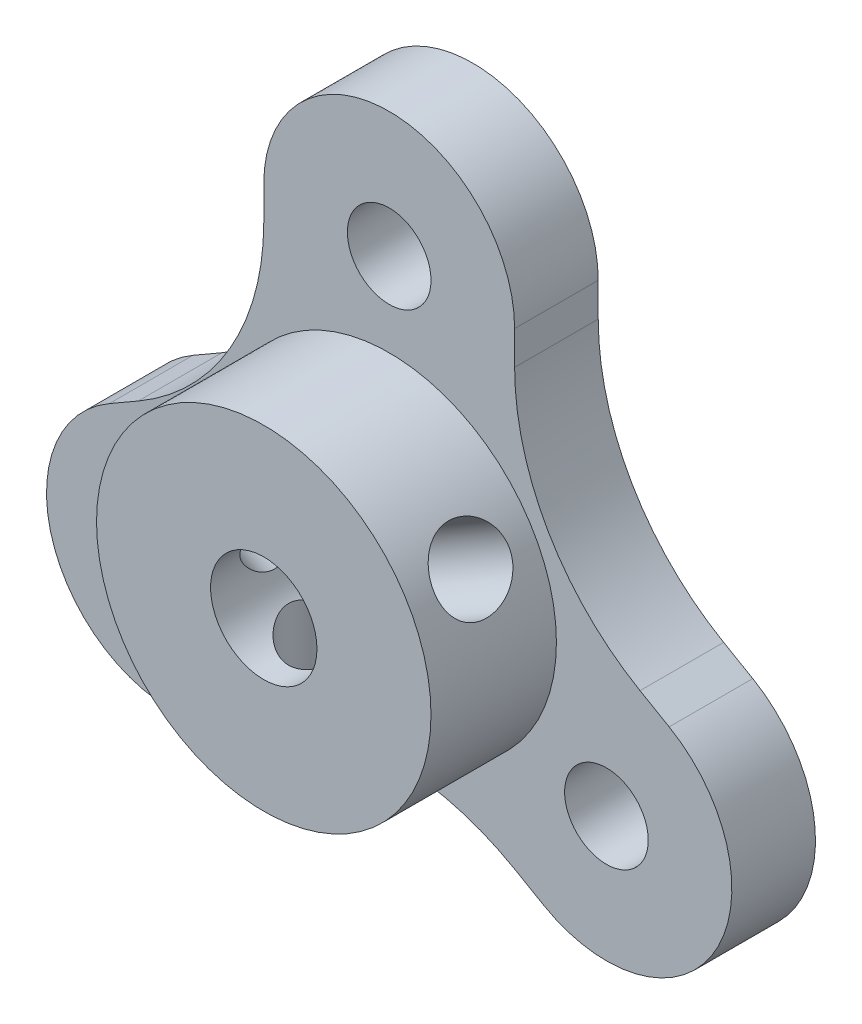
SolidWorks part; units mm, degrees
material "6061-T6 (SS)"
ref_plane "Front Plane" through (0, 0, 0) normal (0, 0, 1) x (1, 0, 0)
ref_plane "Top Plane" through (0, 0, 0) normal (0, 1, 0) x (1, 0, 0)
ref_plane "Right Plane" through (0, 0, 0) normal (1, 0, 0) x (0, 0, -1)
sketch "Sketch1" plane through (0, 0, 0) normal (1, 0, 0) x (0, 0, -1)
  line L0 (0, 2.0193) -> (0, 6.35)
  line L1 (0, 6.35) -> (4.7625, 6.35)
  line L3 (4.7625, 6.35) -> (4.7625, 15.875)
  line L4 (7.9375, 15.875) -> (7.9375, 2.0193)
  line L5 (0, 2.0193) -> (7.9375, 2.0193)
  line L6 (4.7625, 15.875) -> (7.9375, 15.875)
  line L7 (0, 0) -> (10.5039, 0) construction
  dimension "D1" = 2.0193
  dimension "D2" = 6.35
  dimension "D3" = 4.7625
  dimension "D4" = 3.175
  dimension "D5" = 15.875
revolve "Revolve1" add sketch "Sketch1" angle 360 about L7
hole_wizard "1/8 (0.1250) Dowel Hole1" positions "Sketch2" profile "Sketch3" hole size "1/8" standard "ANSI Inch" end condition through all
sketch "Sketch2" plane through (0, 0, -4.7625) normal (0, 0, 1) x (1, 0, 0)
  point P0 (0, 9.525)
  point P9 (0, 0)
  dimension "D2" = 9.525
sketch "Sketch3" plane through (0, 9.525, -4.7625) normal (1, 0, 0) x (0, -1, 0)
  line L0 (0, 0) -> (0, 3.175)
  line L1 (0, 3.175) -> (1.5875, 3.175)
  line L2 (1.5875, 3.175) -> (1.5875, 0)
  line L5 (1.5875, 0) -> (0, 0)
  line L11 (0, -6.35) -> (0, 107.95) construction
  dimension "Thru Hole Dia." = 3.175
  dimension "Thru Hole Depth" = 3.175
hole_wizard "#6-40 Tapped Hole1" positions "Sketch4" profile "Sketch6" tap size "#6-40" standard "ANSI Inch"
sketch "Sketch4" plane through (0, 0, 0) normal (0, 1, 0) x (1, 0, 0)
  point P0 (0, 2.3813)
  dimension "D1" = 2.3813
sketch "Sketch6" plane through (0, 0, -2.3813) normal (1, 0, 0) x (0, 0, 1)
  line L0 (0, 0) -> (0, 21.6857)
  line L1 (0, 21.6857) -> (1.4351, 21.6857)
  line L2 (1.4351, 21.6857) -> (1.4351, 0)
  line L5 (1.4351, 0) -> (0, 0)
  line L11 (0, -6.35) -> (0, 107.95) construction
  dimension "Thru Tap Drill Dia." = 2.8702
  dimension "Thru Tap Drill Depth" = 21.6857
cosmetic thread "Hole Thread2" parameters "D2"=3.5052
pattern_circular "CirPattern1" count 3 over 360 about axis through (0, 0, 0) along (0, 0, 1) of "#6-40 Tapped Hole1"
pattern_circular "CirPattern2" count 3 over 360 about axis through (0, 0, 0) along (0, 0, 1) of "1/8 (0.1250) Dowel Hole1"
sketch "Sketch7" plane through (0, 0, -4.7625) normal (0, 0, 1) x (1, 0, 0)
  line L0 (4.7625, 9.525) -> (4.7625, 8.2489)
  line L1 (-4.7625, 9.525) -> (-4.7625, 8.2489)
  line L2 (10.6301, -0.6381) -> (9.525, 0)
  line L3 (-10.6301, -0.6381) -> (-9.525, 0)
  line L4 (5.8676, -8.8869) -> (4.7625, -8.2489)
  line L5 (-5.8676, -8.8869) -> (-4.7625, -8.2489)
  circle A0 centre (-8.2489, -4.7625) radius 1.5875 construction
  circle A1 centre (8.2489, -4.7625) radius 1.5875 construction
  circle A2 centre (0, 9.525) radius 1.5875 construction
  circle A3 centre (-8.2489, -4.7625) radius 1.5875
  circle A4 centre (8.2489, -4.7625) radius 1.5875
  circle A5 centre (0, 9.525) radius 1.5875
  arc A6 (-4.7625, 9.525) -> (4.7625, 9.525) centre (0, 9.525) cw
  arc A7 (5.8676, -8.8869) -> (10.6301, -0.6381) centre (8.2489, -4.7625) ccw
  arc A8 (-5.8676, -8.8869) -> (-10.6301, -0.6381) centre (-8.2489, -4.7625) cw
  arc A9 (-4.7625, -8.2489) -> (4.7625, -8.2489) centre (0, -16.4978) cw
  arc A10 (4.7625, 8.2489) -> (9.525, 0) centre (14.2875, 8.2489) ccw
  arc A11 (-4.7625, 8.2489) -> (-9.525, 0) centre (-14.2875, 8.2489) cw
  circle M5 centre (0, 0) radius 15.875
  dimension "D1" = 4.7625
  dimension "D2" = 4.7625
  dimension "D3" = 4.7625
  dimension "D6" = 9.525
  dimension "D4" = 120
  dimension "D5" = 120
extrude "Cut-Extrude1" cut sketch "Sketch7" against normal blind 10 contours A8 L3 L1 A6 M5 | A7 A6 L0 L2 M5 | L5 A8 A7 L4 M5
fillet "Fillet1" [suppressed] radius 6.35
equation "\"D2@Sketch7\"=\"D1@Sketch7\""
equation "\"D3@Sketch7\"=\"D1@Sketch7\""
